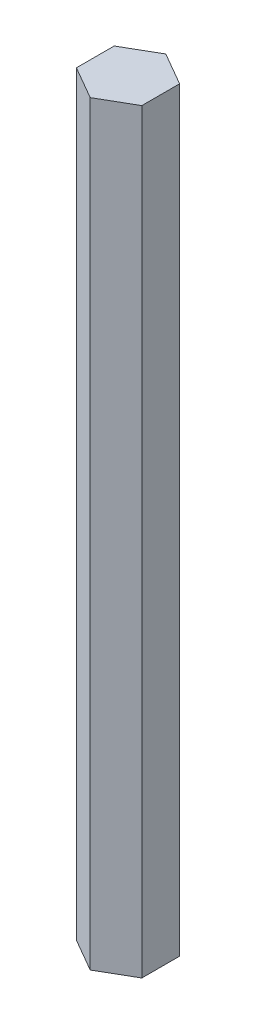
SolidWorks part; units mm, degrees
ref_plane "Front Plane" through (0, 0, 0) normal (0, 0, 1) x (1, 0, 0)
ref_plane "Top Plane" through (0, 0, 0) normal (0, 1, 0) x (1, 0, 0)
ref_plane "Right Plane" through (0, 0, 0) normal (1, 0, 0) x (0, 0, -1)
sketch "Sketch1" plane through (0, 0, 0) normal (0, 1, 0) x (1, 0, 0)
  line L1 (0, -6.35) -> (5.4993, -3.175)
  line L2 (5.4993, -3.175) -> (5.4993, 3.175)
  line L3 (5.4993, 3.175) -> (0, 6.35)
  line L4 (0, 6.35) -> (-5.4993, 3.175)
  line L5 (-5.4993, 3.175) -> (-5.4993, -3.175)
  line L6 (-5.4993, -3.175) -> (0, -6.35)
  circle A0 centre (0, 0) radius 5.4993 construction
  dimension "D1" = 12.7
extrude "Boss-Extrude1" add sketch "Sketch1" along normal blind 127
